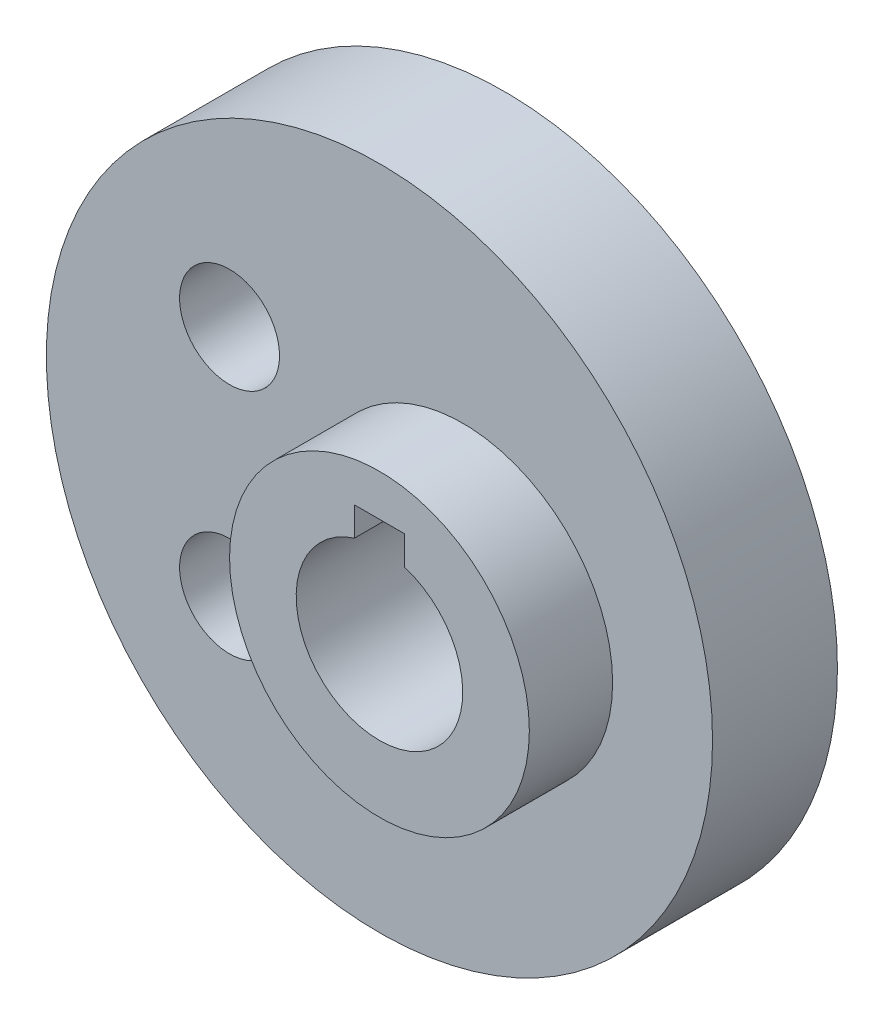
SolidWorks part; units mm, degrees
ref_plane "前视基准面" through (0, 0, 0) normal (0, 0, 1) x (1, 0, 0)
ref_plane "上视基准面" through (0, 0, 0) normal (0, 1, 0) x (1, 0, 0)
ref_plane "右视基准面" through (0, 0, 0) normal (1, 0, 0) x (0, 0, -1)
sketch "草图1" plane through (0, 0, 0) normal (0, 0, 1) x (1, 0, 0)
  circle A0 centre (0, 0) radius 40
extrude "凸台-拉伸1" add sketch "草图1" along normal blind 15
ref_plane "基准面1" through (0, 0, 15) normal (0, 0, 1) x (1, 0, 0)
sketch "草图2" plane through (0, 0, 15) normal (0, 0, 1) x (1, 0, 0)
  circle A0 centre (10, 0) radius 18
extrude "凸台-拉伸2" add sketch "草图2" along normal blind 10
ref_plane "基准面2" through (0, 0, 25) normal (0, 0, 1) x (1, 0, 0)
sketch "草图3" plane through (0, 0, 25) normal (0, 0, 1) x (1, 0, 0)
  circle A0 centre (10, 0) radius 10
extrude "切除-拉伸1" cut sketch "草图3" against normal mid plane 162
sketch "草图4" plane through (0, 0, 25) normal (0, 0, 1) x (1, 0, 0)
  line L0 (7, 0) -> (13, 0)
  line L1 (13, 0) -> (13, 13)
  line L2 (13, 13) -> (7, 13)
  line L3 (7, 13) -> (7, 0)
extrude "切除-拉伸2" cut sketch "草图4" against normal mid plane 162
sketch "草图5" plane through (0, 0, 0) normal (0, 0, 1) x (1, 0, 0)
  circle A0 centre (-18, 14) radius 6
  circle A1 centre (-18, -14) radius 6
extrude "切除-拉伸3" cut sketch "草图5" along normal through all
